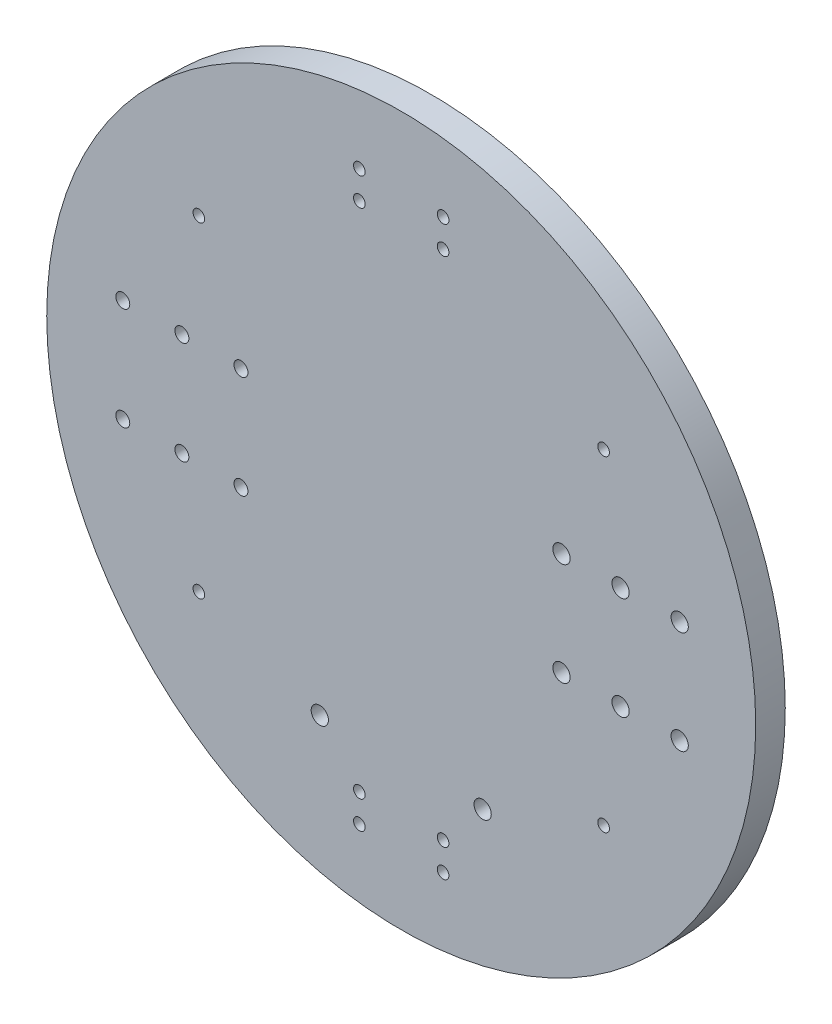
SolidWorks part; units mm, degrees
ref_plane "Front Plane" through (0, 0, 0) normal (0, 0, 1) x (1, 0, 0)
ref_plane "Top Plane" through (0, 0, 0) normal (0, 1, 0) x (1, 0, 0)
ref_plane "Right Plane" through (0, 0, 0) normal (1, 0, 0) x (0, 0, -1)
sketch "Sketch1" plane through (0, 0, 0) normal (0, 0, 1) x (1, 0, 0)
  circle A0 centre (0, 0) radius 76.2
  dimension "D1" = 152.4
extrude "Boss-Extrude1" add sketch "Sketch1" along normal blind 6.35 contours A0
sketch "Sketch2" plane through (0, 0, 6.35) normal (0, 0, 1) x (1, 0, 0)
  line L0 (0, 0) -> (0, 58) construction
  line L1 (43.5, -35) -> (-43.5, -35) construction
  line L2 (43.5, -35) -> (43.5, 35) construction
  line L3 (43.5, 35) -> (-43.5, 35) construction
  line L4 (-43.5, -35) -> (-43.5, 35) construction
  line L5 (43.5, -35) -> (-43.5, 35) construction
  line L6 (43.5, 35) -> (-43.5, -35) construction
  line L7 (0, 0) -> (0, -45) construction
  line L8 (-9, 61) -> (9, 61) construction
  line L9 (-9, 61) -> (-9, 55) construction
  line L10 (-9, 55) -> (9, 55) construction
  line L11 (9, 61) -> (9, 55) construction
  line L12 (-9, 61) -> (9, 55) construction
  line L13 (-9, 55) -> (9, 61) construction
  line L14 (0, -45) -> (17.5, -45) construction
  line L15 (9, -55) -> (-9, -55) construction
  line L16 (9, -55) -> (9, -61) construction
  line L17 (9, -61) -> (-9, -61) construction
  line L18 (-9, -55) -> (-9, -61) construction
  line L19 (9, -55) -> (-9, -61) construction
  line L20 (9, -61) -> (-9, -55) construction
  line L25 (0, -45) -> (-17.5, -45) construction
  circle A0 centre (-43.5, 35) radius 1.25
  circle A1 centre (43.5, 35) radius 1.25
  circle A2 centre (-43.5, -35) radius 1.25
  circle A3 centre (43.5, -35) radius 1.25
  circle A4 centre (17.5, -45) radius 1.855
  circle A5 centre (-17.5, -45) radius 1.855
  circle A6 centre (9, -61) radius 1.25
  circle A7 centre (-9, -61) radius 1.25
  circle A8 centre (-9, -55) radius 1.25
  circle A9 centre (9, -55) radius 1.25
  point P0 (0, 0)
  dimension "D3" = 2.5
  dimension "D4" = 2.5
  dimension "D5" = 2.5
  dimension "D6" = 2.5
  dimension "D15" = 3.71
  dimension "D16" = 3.71
  dimension "D17" = 2.5
  dimension "D18" = 2.5
  dimension "D19" = 2.5
  dimension "D20" = 2.5
  dimension "D1" = 70
  dimension "D2" = 87
  dimension "D7" = 58
  dimension "D8" = 6
  dimension "D9" = 18
  dimension "D10" = 45
  dimension "D11" = 6
  dimension "D12" = 18
  dimension "D13" = 17.5
  dimension "D14" = 17.5
extrude "Cut-Extrude1" cut sketch "Sketch2" against normal through all
sketch "Sketch3" plane through (0, 0, 0) normal (0, 0, -1) x (-1, 0, 0)
  line L0 (0, 0) -> (-34.45, 0) construction
  line L1 (-34.45, 0) -> (-34.45, -11.05) construction
  line L2 (-34.45, 0) -> (-34.45, 11.05) construction
  line L3 (-34.45, 0) -> (-47.15, 0) construction
  line L4 (-47.15, 0) -> (-47.15, 11.05) construction
  line L5 (-47.15, 0) -> (-47.15, -11.05) construction
  line L6 (-47.15, 0) -> (-59.85, 0) construction
  line L7 (-59.85, 0) -> (-59.85, 11.05) construction
  line L8 (-59.85, 0) -> (-59.85, -11.05) construction
  circle A0 centre (-59.85, 11.05) radius 1.855
  circle A1 centre (-47.15, 11.05) radius 1.855
  circle A2 centre (-34.45, 11.05) radius 1.855
  circle A3 centre (-34.45, -11.05) radius 1.855
  circle A4 centre (-47.15, -11.05) radius 1.855
  circle A5 centre (-59.85, -11.05) radius 1.855
  dimension "D8" = 3.71
  dimension "D9" = 3.71
  dimension "D10" = 3.71
  dimension "D11" = 3.71
  dimension "D12" = 3.71
  dimension "D13" = 3.71
  dimension "D1" = 34.45
  dimension "D2" = 11.05
  dimension "D3" = 11.05
  dimension "D4" = 12.7
  dimension "D5" = 11.05
  dimension "D6" = 11.05
  dimension "D7" = 12.7
extrude "Cut-Extrude2" cut sketch "Sketch3" against normal through all
sketch "Sketch5" plane through (0, 0, 0) normal (0, 0, -1) x (-1, 0, 0)
  line L0 (0, 0) -> (34.45, 0) construction
  line L1 (34.45, 0) -> (34.45, 11.05) construction
  line L2 (0, 0) -> (0, 58) construction
  line L3 (0, 0) -> (0, -58) construction
  line L4 (9, 55) -> (-9, 55) construction
  line L5 (9, 55) -> (9, 61) construction
  line L6 (9, 61) -> (-9, 61) construction
  line L7 (-9, 55) -> (-9, 61) construction
  line L8 (9, 55) -> (-9, 61) construction
  line L9 (9, 61) -> (-9, 55) construction
  line L10 (34.45, 11.05) -> (34.45, -11.05) construction
  line L11 (34.45, 11.05) -> (47.15, 11.05) construction
  line L12 (47.15, 11.05) -> (59.85, 11.05) construction
  line L13 (34.45, -11.05) -> (47.15, -11.05) construction
  line L14 (47.15, -11.05) -> (59.85, -11.05) construction
  circle A1 centre (-9, 61) radius 1.25
  circle A2 centre (-9, 55) radius 1.25
  circle A3 centre (9, 61) radius 1.25
  circle A4 centre (9, 55) radius 1.25
  circle A5 centre (34.45, 11.05) radius 1.5
  circle A6 centre (47.15, 11.05) radius 1.5
  circle A7 centre (59.85, 11.05) radius 1.5
  circle A8 centre (59.85, -11.05) radius 1.5
  circle A9 centre (47.15, -11.05) radius 1.5
  circle A10 centre (34.45, -11.05) radius 1.5
extrude "Cut-Extrude3" cut sketch "Sketch5" against normal blind 10
equation "\"s\"=6.35"
